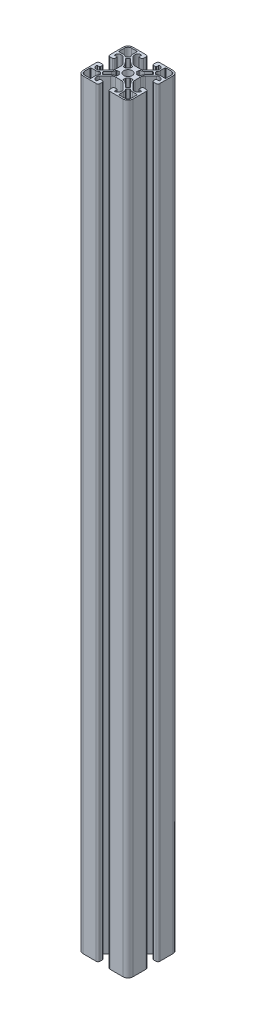
SolidWorks part; units mm, degrees
ref_plane "Front Plane" through (0, 0, 0) normal (0, 0, 1) x (1, 0, 0)
ref_plane "Top Plane" through (0, 0, 0) normal (0, 1, 0) x (1, 0, 0)
ref_plane "Right Plane" through (0, 0, 0) normal (1, 0, 0) x (0, 0, -1)
sketch "Sketch1" plane through (0, 0, 0) normal (0, -1, 0) x (1, 0, 0)
  line L0 (8.9216, 4.9716) -> (13.3642, 9.4142)
  line L1 (14.7784, 10) -> (15.5, 10)
  line L2 (17.5, 7) -> (16, 7)
  line L3 (15.5, 6.5) -> (15.5, 5)
  line L4 (16.5, 4) -> (18.5, 4)
  line L5 (20, 5.5) -> (20, 16)
  line L7 (16, 20) -> (5.5, 20)
  line L8 (4, 18.5) -> (4, 16.5)
  line L9 (5, 15.5) -> (6.5, 15.5)
  line L10 (7, 16) -> (7, 17.5)
  line L11 (10, 15.5) -> (10, 14.7784)
  line L12 (9.4142, 13.3642) -> (4.9716, 8.9216)
  line L13 (2.5, 6.181) -> (2.5, 4.6125)
  line L21 (10.8696, 9.4984) -> (9.4984, 10.8696)
  line L22 (4.6126, 2.5) -> (6.181, 2.5)
  line L23 (10.5378, 12.7378) -> (10.3098, 12.4411)
  line L24 (11.2, 18.3) -> (11.2, 14.6871)
  line L25 (16, 18.8) -> (11.7, 18.8)
  line L26 (18.8, 11.7) -> (18.8, 16)
  line L27 (14.6871, 11.2) -> (18.3, 11.2)
  line L37 (12.4411, 10.3098) -> (12.7378, 10.5378)
  line L38 (10.3528, 11.783) -> (11.783, 10.3528)
  line L39 (4.9716, -8.9216) -> (9.4142, -13.3642)
  line L43 (10, -14.7784) -> (10, -15.5)
  line L44 (7, -17.5) -> (7, -16)
  line L45 (6.5, -15.5) -> (5, -15.5)
  line L47 (4, -16.5) -> (4, -18.5)
  line L48 (5.5, -20) -> (16, -20)
  line L49 (20, -16) -> (20, -5.5)
  line L50 (18.5, -4) -> (16.5, -4)
  line L51 (15.5, -5) -> (15.5, -6.5)
  line L52 (16, -7) -> (17.5, -7)
  line L53 (15.5, -10) -> (14.7784, -10)
  line L54 (13.3642, -9.4142) -> (8.9216, -4.9716)
  line L55 (6.181, -2.5) -> (4.6125, -2.5)
  line L56 (9.4984, -10.8696) -> (10.8696, -9.4984)
  line L57 (2.5, -4.6126) -> (2.5, -6.181)
  line L58 (12.7378, -10.5378) -> (12.4411, -10.3098)
  line L59 (18.3, -11.2) -> (14.6871, -11.2)
  line L60 (18.8, -16) -> (18.8, -11.7)
  line L61 (11.7, -18.8) -> (16, -18.8)
  line L62 (11.2, -14.6871) -> (11.2, -18.3)
  line L63 (10.3098, -12.4411) -> (10.5378, -12.7378)
  line L64 (11.783, -10.3528) -> (10.3528, -11.783)
  line L65 (-8.9216, -4.9716) -> (-13.3642, -9.4142)
  line L66 (-14.7784, -10) -> (-15.5, -10)
  line L67 (-17.5, -7) -> (-16, -7)
  line L68 (-15.5, -6.5) -> (-15.5, -5)
  line L69 (-16.5, -4) -> (-18.5, -4)
  line L70 (-20, -5.5) -> (-20, -16)
  line L71 (-16, -20) -> (-5.5, -20)
  line L72 (-4, -18.5) -> (-4, -16.5)
  line L73 (-5, -15.5) -> (-6.5, -15.5)
  line L74 (-7, -16) -> (-7, -17.5)
  line L75 (-10, -15.5) -> (-10, -14.7784)
  line L76 (-9.4142, -13.3642) -> (-4.9716, -8.9216)
  line L77 (-2.5, -6.181) -> (-2.5, -4.6125)
  line L78 (-10.8696, -9.4984) -> (-9.4984, -10.8696)
  line L79 (-4.6126, -2.5) -> (-6.181, -2.5)
  line L80 (-10.5378, -12.7378) -> (-10.3098, -12.4411)
  line L81 (-11.2, -18.3) -> (-11.2, -14.6871)
  line L82 (-16, -18.8) -> (-11.7, -18.8)
  line L83 (-18.8, -11.7) -> (-18.8, -16)
  line L84 (-14.6871, -11.2) -> (-18.3, -11.2)
  line L85 (-12.4411, -10.3098) -> (-12.7378, -10.5378)
  line L86 (-10.3528, -11.783) -> (-11.783, -10.3528)
  line L87 (-2.1431, 7.75) -> (2.1431, 7.75)
  line L88 (7.75, 2.1431) -> (7.75, -2.1431)
  line L89 (2.1431, -7.75) -> (-2.1431, -7.75)
  line L90 (-7.75, -2.1431) -> (-7.75, 2.1431)
  line L125 (-4.9716, 8.9216) -> (-9.4142, 13.3642)
  line L126 (-10, 14.7784) -> (-10, 15.5)
  line L127 (-7, 17.5) -> (-7, 16)
  line L128 (-6.5, 15.5) -> (-5, 15.5)
  line L129 (-4, 16.5) -> (-4, 18.5)
  line L130 (-5.5, 20) -> (-16, 20)
  line L131 (-20, 16) -> (-20, 5.5)
  line L132 (-18.5, 4) -> (-16.5, 4)
  line L133 (-15.5, 5) -> (-15.5, 6.5)
  line L134 (-16, 7) -> (-17.5, 7)
  line L135 (-15.5, 10) -> (-14.7784, 10)
  line L136 (-13.3642, 9.4142) -> (-8.9216, 4.9716)
  line L170 (-6.181, 2.5) -> (-4.6125, 2.5)
  line L171 (-9.4984, 10.8696) -> (-10.8696, 9.4984)
  line L172 (-2.5, 4.6126) -> (-2.5, 6.181)
  line L184 (-12.7378, 10.5378) -> (-12.4411, 10.3098)
  line L185 (-18.3, 11.2) -> (-14.6871, 11.2)
  line L186 (-18.8, 16) -> (-18.8, 11.7)
  line L187 (-11.7, 18.8) -> (-16, 18.8)
  line L188 (-11.2, 14.6871) -> (-11.2, 18.3)
  line L189 (-10.3098, 12.4411) -> (-10.5378, 12.7378)
  line L190 (-11.783, 10.3528) -> (-10.3528, 11.783)
  arc A0 (0, 3.4) -> (0, -3.4) centre (0, 0) ccw
  arc A1 (0, -3.4) -> (0, 3.4) centre (0, 0) ccw
  arc A2 (8.9216, 4.9716) -> (7.75, 2.1431) centre (11.75, 2.1431) ccw
  arc A3 (14.7784, 10) -> (13.3642, 9.4142) centre (14.7784, 8) ccw
  arc A4 (-3.4, 0) -> (3.4, 0) centre (0, 0) ccw
  arc A5 (3.4, 0) -> (-3.4, 0) centre (0, 0) ccw
  arc A6 (18, 7.5) -> (15.5, 10) centre (15.5, 7.5) ccw
  arc A7 (17.5, 7) -> (18, 7.5) centre (17.5, 7.5) ccw
  arc A8 (16, 7) -> (15.5, 6.5) centre (16, 6.5) ccw
  arc A9 (15.5, 5) -> (16.5, 4) centre (16.5, 5) ccw
  arc A10 (18.5, 4) -> (20, 5.5) centre (18.5, 5.5) ccw
  arc A11 (20, 16) -> (16, 20) centre (16, 16) ccw
  arc A12 (5.5, 20) -> (4, 18.5) centre (5.5, 18.5) ccw
  arc A13 (4, 16.5) -> (5, 15.5) centre (5, 16.5) ccw
  arc A21 (6.5, 15.5) -> (7, 16) centre (6.5, 16) ccw
  arc A22 (7.5, 18) -> (7, 17.5) centre (7.5, 17.5) ccw
  arc A23 (10, 15.5) -> (7.5, 18) centre (7.5, 15.5) ccw
  arc A24 (9.4142, 13.3642) -> (10, 14.7784) centre (8, 14.7784) ccw
  arc A25 (2.1431, 7.75) -> (4.9716, 8.9216) centre (2.1431, 11.75) ccw
  arc A26 (2.5, 4.6125) -> (2.7274, 4.1934) centre (3, 4.6125) ccw
  arc A27 (2.9293, 6.676) -> (2.5, 6.181) centre (3, 6.181) ccw
  arc A35 (2.9293, 6.676) -> (5.3722, 7.7078) centre (2.1944, 11.8238) ccw
  arc A36 (5.3722, 7.7078) -> (8.7744, 10.8518) centre (-10.6389, 28.4463) ccw
  arc A37 (9.4984, 10.8696) -> (8.7744, 10.8518) centre (9.1449, 10.516) ccw
  arc A38 (10.8518, 8.7744) -> (10.8696, 9.4984) centre (10.516, 9.1449) ccw
  arc A39 (10.8518, 8.7744) -> (7.7078, 5.3722) centre (28.4463, -10.6389) ccw
  arc A40 (7.7078, 5.3722) -> (6.676, 2.9293) centre (11.8238, 2.1944) ccw
  arc A41 (6.181, 2.5) -> (6.676, 2.9293) centre (6.181, 3) ccw
  arc A42 (4.1934, 2.7274) -> (4.6126, 2.5) centre (4.6126, 3) ccw
  arc A43 (4.1934, 2.7274) -> (2.7274, 4.1934) centre (0.0017, 0.0017) ccw
  arc A44 (10.3098, 12.4411) -> (10.3528, 11.783) centre (10.7064, 12.1365) ccw
  arc A45 (10.5378, 12.7378) -> (11.2, 14.6871) centre (8, 14.6871) ccw
  arc A46 (11.7, 18.8) -> (11.2, 18.3) centre (11.7, 18.3) ccw
  arc A47 (18.8, 16) -> (16, 18.8) centre (16, 16) ccw
  arc A48 (18.3, 11.2) -> (18.8, 11.7) centre (18.3, 11.7) ccw
  arc A49 (14.6871, 11.2) -> (12.7378, 10.5378) centre (14.6871, 8) ccw
  arc A60 (11.783, 10.3528) -> (12.4411, 10.3098) centre (12.1365, 10.7064) ccw
  arc A61 (3.4, 0) -> (-3.4, 0) centre (0, 0) ccw
  arc A62 (-3.4, 0) -> (3.4, 0) centre (0, 0) ccw
  arc A63 (4.9716, -8.9216) -> (2.1431, -7.75) centre (2.1431, -11.75) ccw
  arc A64 (10, -14.7784) -> (9.4142, -13.3642) centre (8, -14.7784) ccw
  arc A65 (7.5, -18) -> (10, -15.5) centre (7.5, -15.5) ccw
  arc A66 (7, -17.5) -> (7.5, -18) centre (7.5, -17.5) ccw
  arc A67 (7, -16) -> (6.5, -15.5) centre (6.5, -16) ccw
  arc A68 (5, -15.5) -> (4, -16.5) centre (5, -16.5) ccw
  arc A69 (4, -18.5) -> (5.5, -20) centre (5.5, -18.5) ccw
  arc A70 (16, -20) -> (20, -16) centre (16, -16) ccw
  arc A71 (20, -5.5) -> (18.5, -4) centre (18.5, -5.5) ccw
  arc A72 (16.5, -4) -> (15.5, -5) centre (16.5, -5) ccw
  arc A73 (15.5, -6.5) -> (16, -7) centre (16, -6.5) ccw
  arc A74 (18, -7.5) -> (17.5, -7) centre (17.5, -7.5) ccw
  arc A75 (15.5, -10) -> (18, -7.5) centre (15.5, -7.5) ccw
  arc A76 (13.3642, -9.4142) -> (14.7784, -10) centre (14.7784, -8) ccw
  arc A77 (7.75, -2.1431) -> (8.9216, -4.9716) centre (11.75, -2.1431) ccw
  arc A78 (4.6125, -2.5) -> (4.1934, -2.7274) centre (4.6125, -3) ccw
  arc A79 (6.676, -2.9293) -> (6.181, -2.5) centre (6.181, -3) ccw
  arc A80 (6.676, -2.9293) -> (7.7078, -5.3722) centre (11.8238, -2.1944) ccw
  arc A81 (7.7078, -5.3722) -> (10.8518, -8.7744) centre (28.4463, 10.6389) ccw
  arc A82 (10.8696, -9.4984) -> (10.8518, -8.7744) centre (10.516, -9.1449) ccw
  arc A83 (8.7744, -10.8518) -> (9.4984, -10.8696) centre (9.1449, -10.516) ccw
  arc A84 (8.7744, -10.8518) -> (5.3722, -7.7078) centre (-10.6389, -28.4463) ccw
  arc A85 (5.3722, -7.7078) -> (2.9293, -6.676) centre (2.1944, -11.8238) ccw
  arc A86 (2.5, -6.181) -> (2.9293, -6.676) centre (3, -6.181) ccw
  arc A87 (2.7274, -4.1934) -> (2.5, -4.6126) centre (3, -4.6126) ccw
  arc A88 (2.7274, -4.1934) -> (4.1934, -2.7274) centre (0.0017, -0.0017) ccw
  arc A89 (12.4411, -10.3098) -> (11.783, -10.3528) centre (12.1365, -10.7064) ccw
  arc A90 (12.7378, -10.5378) -> (14.6871, -11.2) centre (14.6871, -8) ccw
  arc A91 (18.8, -11.7) -> (18.3, -11.2) centre (18.3, -11.7) ccw
  arc A92 (16, -18.8) -> (18.8, -16) centre (16, -16) ccw
  arc A93 (11.2, -18.3) -> (11.7, -18.8) centre (11.7, -18.3) ccw
  arc A94 (11.2, -14.6871) -> (10.5378, -12.7378) centre (8, -14.6871) ccw
  arc A95 (10.3528, -11.783) -> (10.3098, -12.4411) centre (10.7064, -12.1365) ccw
  arc A96 (0, -3.4) -> (0, 3.4) centre (0, 0) ccw
  arc A97 (0, 3.4) -> (0, -3.4) centre (0, 0) ccw
  arc A98 (-8.9216, -4.9716) -> (-7.75, -2.1431) centre (-11.75, -2.1431) ccw
  arc A99 (-14.7784, -10) -> (-13.3642, -9.4142) centre (-14.7784, -8) ccw
  arc A100 (-18, -7.5) -> (-15.5, -10) centre (-15.5, -7.5) ccw
  arc A101 (-17.5, -7) -> (-18, -7.5) centre (-17.5, -7.5) ccw
  arc A102 (-16, -7) -> (-15.5, -6.5) centre (-16, -6.5) ccw
  arc A103 (-15.5, -5) -> (-16.5, -4) centre (-16.5, -5) ccw
  arc A104 (-18.5, -4) -> (-20, -5.5) centre (-18.5, -5.5) ccw
  arc A105 (-20, -16) -> (-16, -20) centre (-16, -16) ccw
  arc A106 (-5.5, -20) -> (-4, -18.5) centre (-5.5, -18.5) ccw
  arc A107 (-4, -16.5) -> (-5, -15.5) centre (-5, -16.5) ccw
  arc A108 (-6.5, -15.5) -> (-7, -16) centre (-6.5, -16) ccw
  arc A109 (-7.5, -18) -> (-7, -17.5) centre (-7.5, -17.5) ccw
  arc A110 (-10, -15.5) -> (-7.5, -18) centre (-7.5, -15.5) ccw
  arc A111 (-9.4142, -13.3642) -> (-10, -14.7784) centre (-8, -14.7784) ccw
  arc A112 (-2.1431, -7.75) -> (-4.9716, -8.9216) centre (-2.1431, -11.75) ccw
  arc A113 (-2.5, -4.6125) -> (-2.7274, -4.1934) centre (-3, -4.6125) ccw
  arc A114 (-2.9293, -6.676) -> (-2.5, -6.181) centre (-3, -6.181) ccw
  arc A115 (-2.9293, -6.676) -> (-5.3722, -7.7078) centre (-2.1944, -11.8238) ccw
  arc A116 (-5.3722, -7.7078) -> (-8.7744, -10.8518) centre (10.6389, -28.4463) ccw
  arc A117 (-9.4984, -10.8696) -> (-8.7744, -10.8518) centre (-9.1449, -10.516) ccw
  arc A118 (-10.8518, -8.7744) -> (-10.8696, -9.4984) centre (-10.516, -9.1449) ccw
  arc A119 (-10.8518, -8.7744) -> (-7.7078, -5.3722) centre (-28.4463, 10.6389) ccw
  arc A144 (-4.9716, 8.9216) -> (-2.1431, 7.75) centre (-2.1431, 11.75) ccw
  arc A145 (-10, 14.7784) -> (-9.4142, 13.3642) centre (-8, 14.7784) ccw
  arc A146 (-7.5, 18) -> (-10, 15.5) centre (-7.5, 15.5) ccw
  arc A147 (-7, 17.5) -> (-7.5, 18) centre (-7.5, 17.5) ccw
  arc A148 (-7, 16) -> (-6.5, 15.5) centre (-6.5, 16) ccw
  arc A149 (-5, 15.5) -> (-4, 16.5) centre (-5, 16.5) ccw
  arc A150 (-4, 18.5) -> (-5.5, 20) centre (-5.5, 18.5) ccw
  arc A151 (-16, 20) -> (-20, 16) centre (-16, 16) ccw
  arc A152 (-20, 5.5) -> (-18.5, 4) centre (-18.5, 5.5) ccw
  arc A153 (-16.5, 4) -> (-15.5, 5) centre (-16.5, 5) ccw
  arc A154 (-15.5, 6.5) -> (-16, 7) centre (-16, 6.5) ccw
  arc A155 (-18, 7.5) -> (-17.5, 7) centre (-17.5, 7.5) ccw
  arc A156 (-15.5, 10) -> (-18, 7.5) centre (-15.5, 7.5) ccw
  arc A157 (-13.3642, 9.4142) -> (-14.7784, 10) centre (-14.7784, 8) ccw
  arc A158 (-7.75, 2.1431) -> (-8.9216, 4.9716) centre (-11.75, 2.1431) ccw
  arc A181 (-7.7078, -5.3722) -> (-6.676, -2.9293) centre (-11.8238, -2.1944) ccw
  arc A182 (-6.181, -2.5) -> (-6.676, -2.9293) centre (-6.181, -3) ccw
  arc A183 (-4.1934, -2.7274) -> (-4.6126, -2.5) centre (-4.6126, -3) ccw
  arc A184 (-4.1934, -2.7274) -> (-2.7274, -4.1934) centre (-0.0017, -0.0017) ccw
  arc A185 (-10.3098, -12.4411) -> (-10.3528, -11.783) centre (-10.7064, -12.1365) ccw
  arc A186 (-10.5378, -12.7378) -> (-11.2, -14.6871) centre (-8, -14.6871) ccw
  arc A187 (-11.7, -18.8) -> (-11.2, -18.3) centre (-11.7, -18.3) ccw
  arc A188 (-18.8, -16) -> (-16, -18.8) centre (-16, -16) ccw
  arc A189 (-18.3, -11.2) -> (-18.8, -11.7) centre (-18.3, -11.7) ccw
  arc A190 (-14.6871, -11.2) -> (-12.7378, -10.5378) centre (-14.6871, -8) ccw
  arc A191 (-11.783, -10.3528) -> (-12.4411, -10.3098) centre (-12.1365, -10.7064) ccw
  arc A254 (-4.6125, 2.5) -> (-4.1934, 2.7274) centre (-4.6125, 3) ccw
  arc A255 (-6.676, 2.9293) -> (-6.181, 2.5) centre (-6.181, 3) ccw
  arc A256 (-6.676, 2.9293) -> (-7.7078, 5.3722) centre (-11.8238, 2.1944) ccw
  arc A257 (-7.7078, 5.3722) -> (-10.8518, 8.7744) centre (-28.4463, -10.6389) ccw
  arc A258 (-10.8696, 9.4984) -> (-10.8518, 8.7744) centre (-10.516, 9.1449) ccw
  arc A259 (-8.7744, 10.8518) -> (-9.4984, 10.8696) centre (-9.1449, 10.516) ccw
  arc A260 (-8.7744, 10.8518) -> (-5.3722, 7.7078) centre (10.6389, 28.4463) ccw
  arc A261 (-5.3722, 7.7078) -> (-2.9293, 6.676) centre (-2.1944, 11.8238) ccw
  arc A262 (-2.5, 6.181) -> (-2.9293, 6.676) centre (-3, 6.181) ccw
  arc A263 (-2.7274, 4.1934) -> (-2.5, 4.6126) centre (-3, 4.6126) ccw
  arc A264 (-2.7274, 4.1934) -> (-4.1934, 2.7274) centre (-0.0017, 0.0017) ccw
  arc A268 (-12.4411, 10.3098) -> (-11.783, 10.3528) centre (-12.1365, 10.7064) ccw
  arc A269 (-12.7378, 10.5378) -> (-14.6871, 11.2) centre (-14.6871, 8) ccw
  arc A270 (-18.8, 11.7) -> (-18.3, 11.2) centre (-18.3, 11.7) ccw
  arc A271 (-16, 18.8) -> (-18.8, 16) centre (-16, 16) ccw
  arc A272 (-11.2, 18.3) -> (-11.7, 18.8) centre (-11.7, 18.3) ccw
  arc A273 (-11.2, 14.6871) -> (-10.5378, 12.7378) centre (-8, 14.6871) ccw
  arc A274 (-10.3528, 11.783) -> (-10.3098, 12.4411) centre (-10.7064, 12.1365) ccw
  point P367 (0, 0)
  dimension "D1" = 40
extrude "Boss-Extrude1" add sketch "Sketch1" against normal blind 610 separate body contours L90 A158 L136 A157 L135 A156 A155 L134 A154 L133 A153 L132 A152 L131 A151 L130 A150 L129 A149 L128 A148 L127 A147 A146 L126 A145 L125 A144 L87 A25 L12 A24 L11 A23 A22 L10 A21 L9 A13 L8 A12 L7 A11 L5 A10 L4 A9 L3 A8 L2 A7
